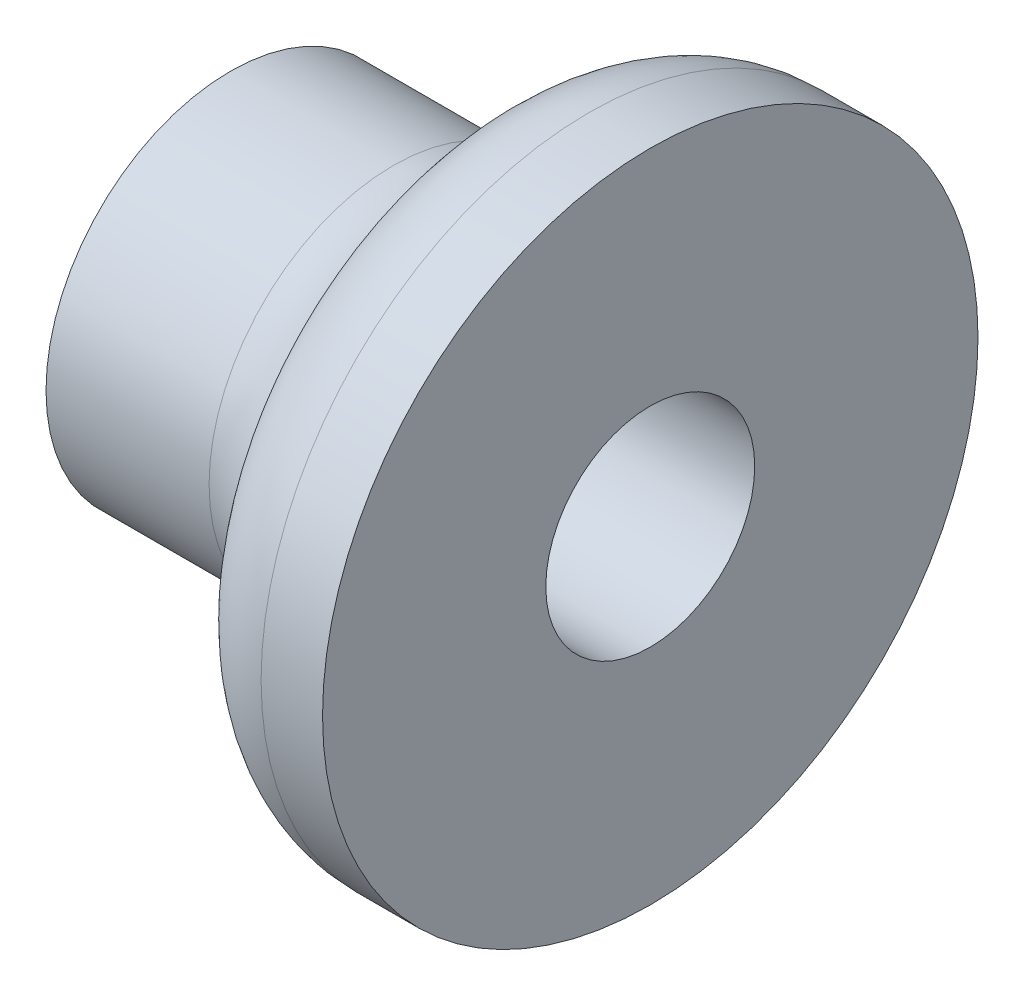
SolidWorks part; units mm, degrees
ref_plane "Front Plane" through (0, 0, 0) normal (0, 0, 1) x (1, 0, 0)
ref_plane "Top Plane" through (0, 0, 0) normal (0, 1, 0) x (1, 0, 0)
ref_plane "Right Plane" through (0, 0, 0) normal (1, 0, 0) x (0, 0, -1)
sketch "Sketch1" plane through (0, 0, 0) normal (1, 0, 0) x (0, 0, -1)
  circle A0 centre (0, 0) radius 4.5
  dimension "D1" = 9
extrude "Boss-Extrude1" add sketch "Sketch1" along normal blind 10.25
sketch "Sketch3" plane through (0, 0, 0) normal (-1, 0, 0) x (0, 0, 1)
  circle A0 centre (0, 0) radius 2.55
  dimension "D1" = 5.1
extrude "Cut-Extrude1" cut sketch "Sketch3" against normal blind 34
sketch "Sketch4" plane through (10.25, 0, 0) normal (1, 0, 0) x (0, 0, -1)
  circle A0 centre (0, 0) radius 8
  circle A1 centre (0, 0) radius 4.5 construction
  circle A2 centre (0, 0) radius 4.5
  dimension "D1" = 16
extrude "Boss-Extrude2" add sketch "Sketch4" against normal blind 4
fillet "Fillet1" radius 2.5 1 edges at (6.25, 0, -8)
fillet "Fillet2" radius 2.5 1 edges at (6.25, 0, -4.5)
sketch "Sketch5" plane through (0, 0, 0) normal (-1, 0, 0) x (0, 0, 1)
  circle A0 centre (0, 0) radius 3
  circle A1 centre (0, 0) radius 2.55 construction
  circle A2 centre (0, 0) radius 2.55
  dimension "D1" = 6
extrude "Cut-Extrude2" cut sketch "Sketch5" against normal blind 0.7
